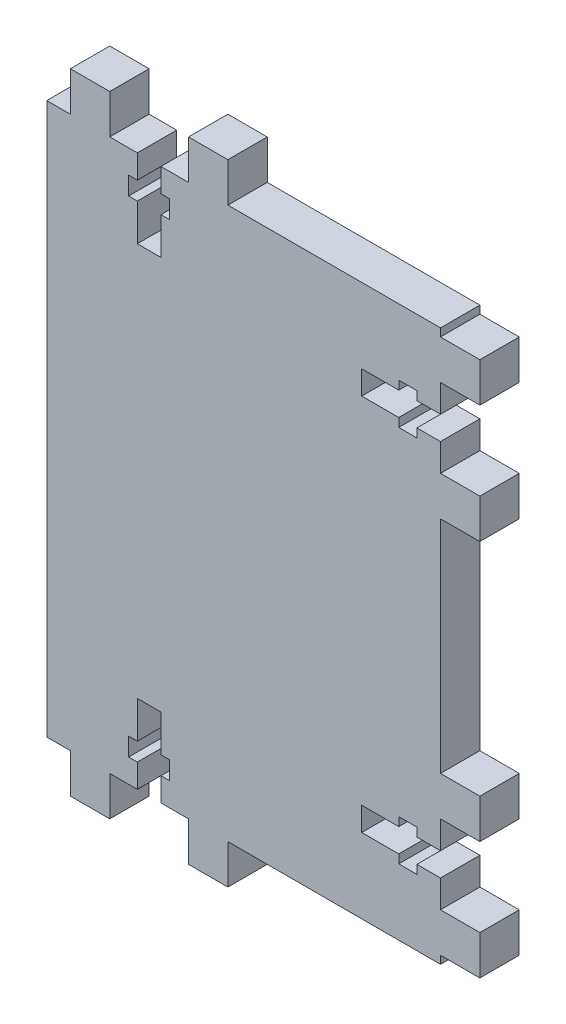
SolidWorks part; units mm, degrees
ref_plane "Plan de face" through (0, 0, 0) normal (0, 0, 1) x (1, 0, 0)
ref_plane "Plan de dessus" through (0, 0, 0) normal (0, 1, 0) x (1, 0, 0)
ref_plane "Plan de droite" through (0, 0, 0) normal (1, 0, 0) x (0, 0, -1)
sketch "Esquisse1" plane through (0, 0, 0) normal (0, 0, 1) x (1, 0, 0)
  line L0 (23, 0) -> (50, 0)
  line L1 (0, 0) -> (50, 0) construction
  line L2 (0, 0) -> (0, 70)
  line L3 (0, 70) -> (50, 70) construction
  line L4 (50, 0) -> (50, 70) construction
  line L5 (3, 0) -> (0, 0)
  line L6 (23, 70) -> (50, 70)
  line L7 (3, 70) -> (0, 70)
  line L8 (13, 70) -> (13, 58.7792) construction
  line L9 (14.5, 70) -> (18, 70)
  line L10 (18, 75) -> (23, 75)
  line L11 (23, 75) -> (23, 70)
  line L12 (18, 75) -> (18, 70)
  line L13 (11.5, 70) -> (8, 70)
  line L14 (8, 70) -> (8, 75)
  line L15 (8, 75) -> (3, 75)
  line L16 (3, 75) -> (3, 70)
  line L17 (14.5, 70) -> (11.5, 70) construction
  line L18 (11.5, 70) -> (11.5, 67)
  line L19 (11.5, 64.7) -> (10.4, 64.7)
  line L20 (15.6, 67) -> (15.6, 64.7)
  line L21 (10.4, 67) -> (11.5, 67)
  line L22 (11.5, 64.7) -> (11.5, 60)
  line L23 (11.5, 60) -> (14.5, 60)
  line L24 (14.5, 60) -> (14.5, 64.7)
  line L25 (14.5, 67) -> (15.6, 67)
  line L26 (10.4, 64.7) -> (10.4, 67)
  line L27 (15.6, 64.7) -> (14.5, 64.7)
  line L28 (14.5, 67) -> (14.5, 70)
  line L29 (13, 60) -> (13, 70) construction
  line L30 (13, 0) -> (13, 11.2208) construction
  line L31 (11.5, 0) -> (8, 0)
  line L32 (8, -5) -> (3, -5)
  line L33 (3, -5) -> (3, 0)
  line L34 (8, -5) -> (8, 0)
  line L35 (14.5, 0) -> (18, 0)
  line L36 (18, 0) -> (18, -5)
  line L37 (18, -5) -> (23, -5)
  line L38 (23, -5) -> (23, 0)
  line L39 (11.5, 0) -> (14.5, 0) construction
  line L40 (14.5, 0) -> (14.5, 3)
  line L41 (14.5, 5.3) -> (15.6, 5.3)
  line L42 (10.4, 3) -> (10.4, 5.3)
  line L43 (15.6, 3) -> (14.5, 3)
  line L44 (14.5, 5.3) -> (14.5, 10)
  line L45 (14.5, 10) -> (11.5, 10)
  line L46 (11.5, 10) -> (11.5, 5.3)
  line L47 (11.5, 3) -> (10.4, 3)
  line L48 (15.6, 5.3) -> (15.6, 3)
  line L49 (10.4, 5.3) -> (11.5, 5.3)
  line L50 (11.5, 3) -> (11.5, 0)
  line L51 (13, 10) -> (13, 0) construction
  line L52 (50, 70) -> (50, 69)
  line L53 (50, 49) -> (50, 21)
  line L54 (50, 1) -> (50, 0)
  line L55 (50, 11) -> (38.7792, 11) construction
  line L56 (50, 9.5) -> (50, 6)
  line L57 (55, 6) -> (55, 1)
  line L58 (55, 1) -> (50, 1)
  line L59 (55, 6) -> (50, 6)
  line L60 (50, 12.5) -> (50, 16)
  line L61 (50, 16) -> (55, 16)
  line L62 (55, 16) -> (55, 21)
  line L63 (55, 21) -> (50, 21)
  line L64 (50, 9.5) -> (50, 12.5) construction
  line L65 (50, 12.5) -> (47, 12.5)
  line L66 (44.7, 12.5) -> (44.7, 13.6)
  line L67 (47, 8.4) -> (44.7, 8.4)
  line L68 (47, 13.6) -> (47, 12.5)
  line L69 (44.7, 12.5) -> (40, 12.5)
  line L70 (40, 12.5) -> (40, 9.5)
  line L71 (40, 9.5) -> (44.7, 9.5)
  line L72 (47, 9.5) -> (47, 8.4)
  line L73 (44.7, 13.6) -> (47, 13.6)
  line L74 (44.7, 8.4) -> (44.7, 9.5)
  line L75 (47, 9.5) -> (50, 9.5)
  line L76 (40, 11) -> (50, 11) construction
  line L77 (50, 59) -> (38.7792, 59) construction
  line L78 (50, 57.5) -> (50, 54)
  line L79 (55, 54) -> (55, 49)
  line L80 (55, 49) -> (50, 49)
  line L81 (55, 54) -> (50, 54)
  line L82 (50, 60.5) -> (50, 64)
  line L83 (50, 64) -> (55, 64)
  line L84 (55, 64) -> (55, 69)
  line L85 (55, 69) -> (50, 69)
  line L86 (50, 57.5) -> (50, 60.5) construction
  line L87 (50, 60.5) -> (47, 60.5)
  line L88 (44.7, 60.5) -> (44.7, 61.6)
  line L89 (47, 56.4) -> (44.7, 56.4)
  line L90 (47, 61.6) -> (47, 60.5)
  line L91 (44.7, 60.5) -> (40, 60.5)
  line L92 (40, 60.5) -> (40, 57.5)
  line L93 (40, 57.5) -> (44.7, 57.5)
  line L94 (47, 57.5) -> (47, 56.4)
  line L95 (44.7, 61.6) -> (47, 61.6)
  line L96 (44.7, 56.4) -> (44.7, 57.5)
  line L97 (47, 57.5) -> (50, 57.5)
  line L98 (40, 59) -> (50, 59) construction
  point P11 (23, -2.5)
  dimension "D1" = 70
  dimension "D2" = 27
  dimension "D3" = 50
  dimension "D4" = 10
  dimension "D5" = 5
  dimension "D6" = 5
  dimension "D7" = 5.2
  dimension "D8" = 3
  dimension "D9" = 2.3
  dimension "D10" = 3
  dimension "D11" = 10
  dimension "D12" = 10
  dimension "D13" = 5
  dimension "D14" = 5
  dimension "D15" = 5.2
  dimension "D16" = 3
  dimension "D17" = 2.3
  dimension "D18" = 3
  dimension "D19" = 10
  dimension "D20" = 11
  dimension "D21" = 48
  dimension "D22" = 10
  dimension "D23" = 5
  dimension "D24" = 5
  dimension "D25" = 5.2
  dimension "D26" = 3
  dimension "D27" = 2.3
  dimension "D28" = 3
  dimension "D29" = 10
  dimension "D30" = 10
  dimension "D31" = 5
  dimension "D32" = 5
  dimension "D33" = 5.2
  dimension "D34" = 3
  dimension "D35" = 2.3
  dimension "D36" = 3
  dimension "D37" = 10
extrude "Boss.-Extru.1" add sketch "Esquisse1" along normal blind 5
